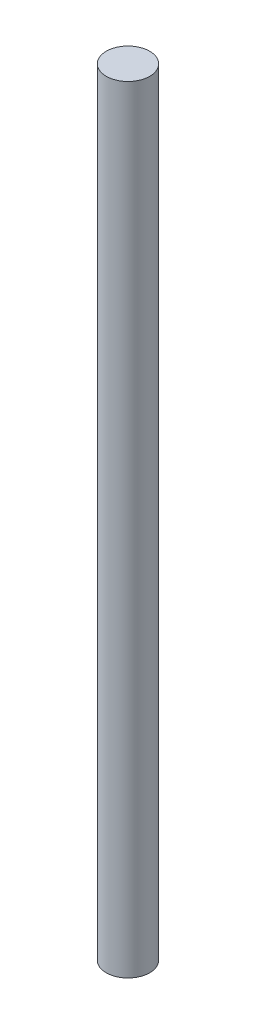
SolidWorks part; units mm, degrees
ref_plane "Front Plane" through (0, 0, 0) normal (0, 0, 1) x (1, 0, 0)
ref_plane "Top Plane" through (0, 0, 0) normal (0, 1, 0) x (1, 0, 0)
ref_plane "Right Plane" through (0, 0, 0) normal (1, 0, 0) x (0, 0, -1)
sketch "Sketch1" plane through (0, 0, 0) normal (0, 1, 0) x (1, 0, 0)
  circle A0 centre (0, 0) radius 0.7
  dimension "D1" = 1.4
extrude "Boss-Extrude1" add sketch "Sketch1" along normal blind 25
